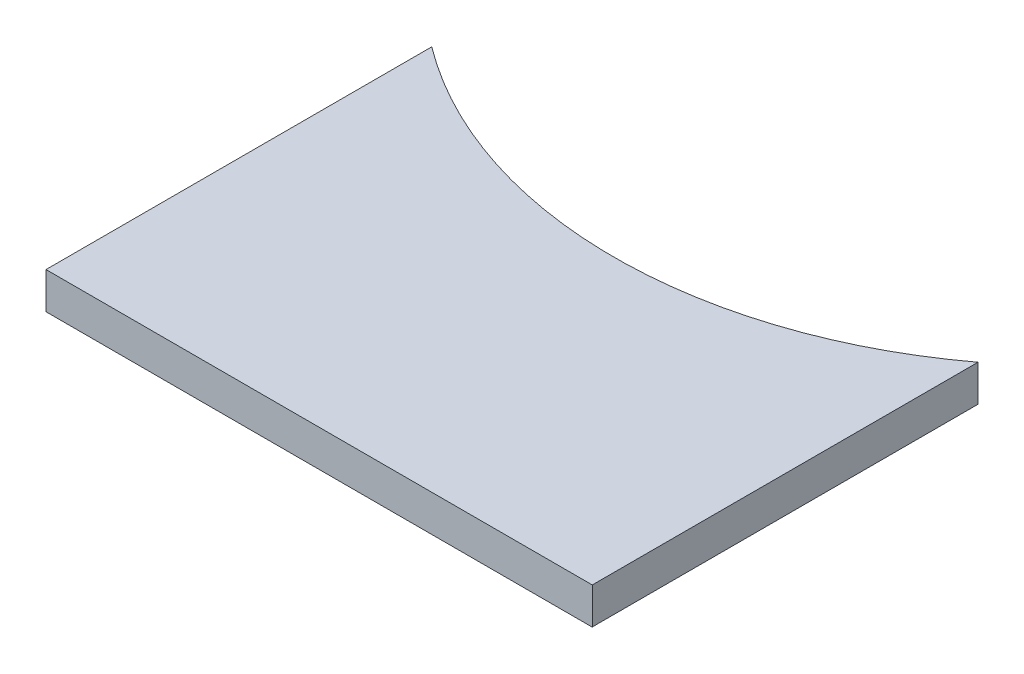
SolidWorks part; units mm, degrees
ref_plane "Front Plane" through (0, 0, 0) normal (0, 0, 1) x (1, 0, 0)
ref_plane "Top Plane" through (0, 0, 0) normal (0, 1, 0) x (1, 0, 0)
ref_plane "Right Plane" through (0, 0, 0) normal (1, 0, 0) x (0, 0, -1)
sketch "Sketch1" plane through (0, 0, 0) normal (0, 1, 0) x (1, 0, 0)
  line L1 (-15, 12.5) -> (15, 12.5)
  line L2 (-15, 12.5) -> (-15, -12.5)
  line L3 (-15, -12.5) -> (15, -12.5)
  line L4 (15, 12.5) -> (15, -12.5)
  line L5 (-15, 12.5) -> (15, -12.5) construction
  line L6 (-15, -12.5) -> (15, 12.5) construction
  point P0 (0, 0)
  dimension "D1" = 25
  dimension "D2" = 30
extrude "Boss-Extrude1" add sketch "Sketch1" along normal blind 2
sketch "Sketch2" plane through (0, 0, 0) normal (0, 1, 0) x (1, 0, 0)
  line L1 (15, -10.5) -> (-15, -10.5)
  line L2 (15, -10.5) -> (15, -12.5)
  line L3 (15, -12.5) -> (-15, -12.5)
  line L4 (-15, -10.5) -> (-15, -12.5)
  line L5 (15, -10.5) -> (-15, -12.5) construction
  line L6 (15, -12.5) -> (-15, -10.5) construction
  point P0 (0, -11.5)
  dimension "D1" = 2
extrude "Boss-Extrude2" add sketch "Sketch2" against normal blind 12.5
sketch "Sketch3" plane through (0, 0, 0) normal (0, 1, 0) x (1, 0, 0)
  circle A0 centre (0, 32.5) radius 25
  dimension "D1" = 50
extrude "Cut-Extrude1" cut sketch "Sketch3" along normal up to next
fillet "Fillet1" radius 2 1 edges at (0, 0, 10.5)
sketch "Sketch4" plane through (0, 2, 0) normal (0, 1, 0) x (1, 0, 0)
  line L2 (-17.7831, -8.6836) -> (17.7831, -8.6836)
  line L3 (-17.7831, -8.6836) -> (-17.7831, -26.3627)
  line L4 (-17.7831, -26.3627) -> (17.7831, -26.3627)
  line L5 (17.7831, -8.6836) -> (17.7831, -26.3627)
  line L6 (-17.7831, -8.6836) -> (17.7831, -26.3627) construction
  line L7 (-17.7831, -26.3627) -> (17.7831, -8.6836) construction
  point P0 (0, -17.5231)
  point P1 (0, -17.5231)
extrude "Cut-Extrude2" cut sketch "Sketch4" against normal up to next
